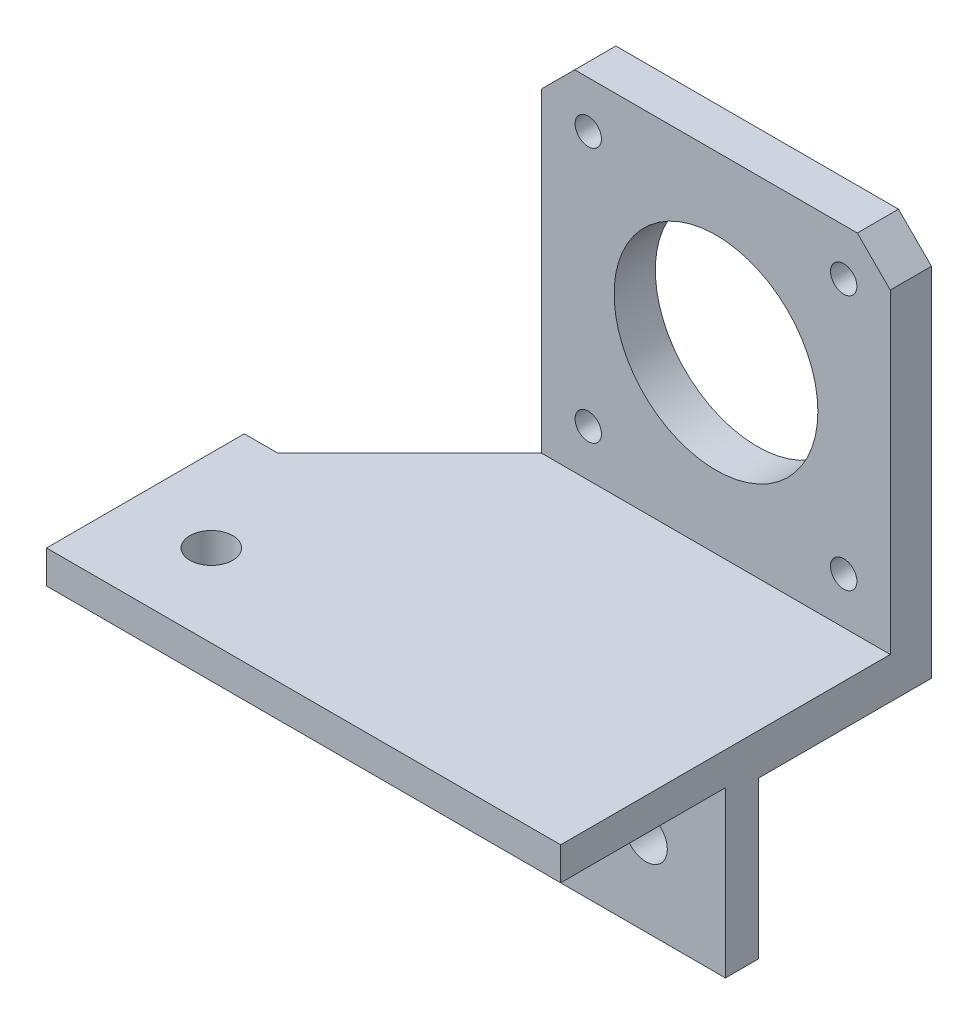
SolidWorks part; units mm, degrees
ref_plane "Přední rovina" through (0, 0, 0) normal (0, 0, 1) x (1, 0, 0)
ref_plane "Horní rovina" through (0, 0, 0) normal (0, 1, 0) x (1, 0, 0)
ref_plane "Pravá rovina" through (0, 0, 0) normal (1, 0, 0) x (0, 0, -1)
sketch "Skica1" plane through (0, 0, 0) normal (0, 0, 1) x (1, 0, 0)
  line L0 (-78.3, 11.0289) -> (-44, 11.0289) construction
  line L1 (-40, -12.9711) -> (-102.3916, -12.9711)
  line L2 (-40, -12.9711) -> (-40, 11.0289)
  line L3 (-40, 11.0289) -> (-102.3916, 11.0289)
  line L4 (-102.3916, -12.9711) -> (-102.3916, 11.0289)
extrude "Přidat vysunutím1" add sketch "Skica1" along normal blind 4
sketch "Skica2" plane through (0, 0, 4) normal (0, 0, 1) x (1, 0, 0)
  line L0 (-82.3, 49.3289) -> (-82.3, 15.0289) construction
  line L1 (-40, 11.0289) -> (-82.3, 11.0289)
  line L2 (-40, 11.0289) -> (-40, 6.0289)
  line L3 (-40, 6.0289) -> (-82.3, 6.0289)
  line L4 (-82.3, 11.0289) -> (-82.3, 6.0289)
  dimension "D1" = 5
extrude "Přidat vysunutím2" add sketch "Skica2" along normal up to surface (16 mm away)
sketch "Skica3" plane through (0, 0, 20) normal (0, 0, 1) x (1, 0, 0)
  line L0 (-82.3, 49.3289) -> (-82.3, 15.0289) construction
  line L1 (-40, 6.0289) -> (-82.3, 6.0289)
  line L2 (-40, 6.0289) -> (-40, 49.3289)
  line L3 (-44, 53.3289) -> (-78.3, 53.3289)
  line L4 (-82.3, 6.0289) -> (-82.3, 49.3289)
  line L5 (-44, 53.3289) -> (-78.3, 53.3289) construction
  line L6 (-40, 49.3289) -> (-44, 53.3289)
  line L7 (-78.3, 53.3289) -> (-82.3, 49.3289)
  circle A0 centre (-45.65, 47.6789) radius 1.6
  circle A1 centre (-76.65, 47.6789) radius 1.6
  circle A2 centre (-76.65, 16.6789) radius 1.6
  circle A3 centre (-45.65, 16.6789) radius 1.6
  circle A4 centre (-61.15, 32.1789) radius 12.3643
  dimension "D1" = 3.2
  dimension "D2" = 2
  dimension "D3" = 2
extrude "Přidat vysunutím5" add sketch "Skica3" along normal blind 5
chamfer "Zkosení1" distance 16 angle 45 1 edges at (-82.3, 8.5289, 4)
sketch "Skica4" plane through (0, 0, 4) normal (0, 0, 1) x (1, 0, 0)
  line L0 (-89.6556, -12.9711) -> (-89.6556, -2.9711) construction
  line L1 (-102.3916, -12.9711) -> (-40, -12.9711) construction
  circle A0 centre (-89.6556, -2.9711) radius 2.6
  circle A1 centre (-69.6556, -2.9711) radius 2.6
  circle A2 centre (-49.6556, -2.9711) radius 2.6
  dimension "D2" = 5.2
  dimension "D1" = 10
  dimension "D3" = 3
extrude "Odebrat vysunutím1" cut sketch "Skica4" against normal blind 4
sketch "Skica5" plane through (0, 0, 0) normal (0, 0, -1) x (-1, 0, 0)
  line L0 (350, 7.0289) -> (0, 7.0289) construction
  line L1 (40, 11.0289) -> (102.3916, 11.0289)
  line L2 (40, 11.0289) -> (40, 7.0289)
  line L3 (40, 7.0289) -> (102.3916, 7.0289)
  line L4 (102.3916, 11.0289) -> (102.3916, 7.0289)
  line L6 (102.3916, 11.0289) -> (102.3916, -12.9711) construction
extrude "Přidat vysunutím6" add sketch "Skica5" along normal up to surface (20 mm away)
sketch "Skica6" plane through (0, 11.0289, 0) normal (0, 1, 0) x (1, 0, 0)
  line L0 (-40, 20) -> (-102.3916, 20) construction
  line L1 (-102.3916, -4) -> (-102.3916, 20) construction
  circle A0 centre (-92.3916, 10) radius 2.6
  dimension "D2" = 5.2
  dimension "D1" = 10
  dimension "D3" = 10
extrude "Odebrat vysunutím2" cut sketch "Skica6" against normal blind 4
mirror "Zrcadlit2" about plane through (-350, -6.1091, -20) normal (0, 0, 1) of bodies 108
sketch "Skica7" plane through (-102.3916, 0, 0) normal (-1, 0, 0) x (0, 0, 1)
  line L1 (-20, -18.6064) -> (32.5479, -18.6064)
  line L2 (-20, -18.6064) -> (-20, 54.7938)
  line L3 (-20, 54.7938) -> (32.5479, 54.7938)
  line L4 (32.5479, -18.6064) -> (32.5479, 54.7938)
extrude "Odebrat vysunutím3" cut sketch "Skica7" against normal blind 80
